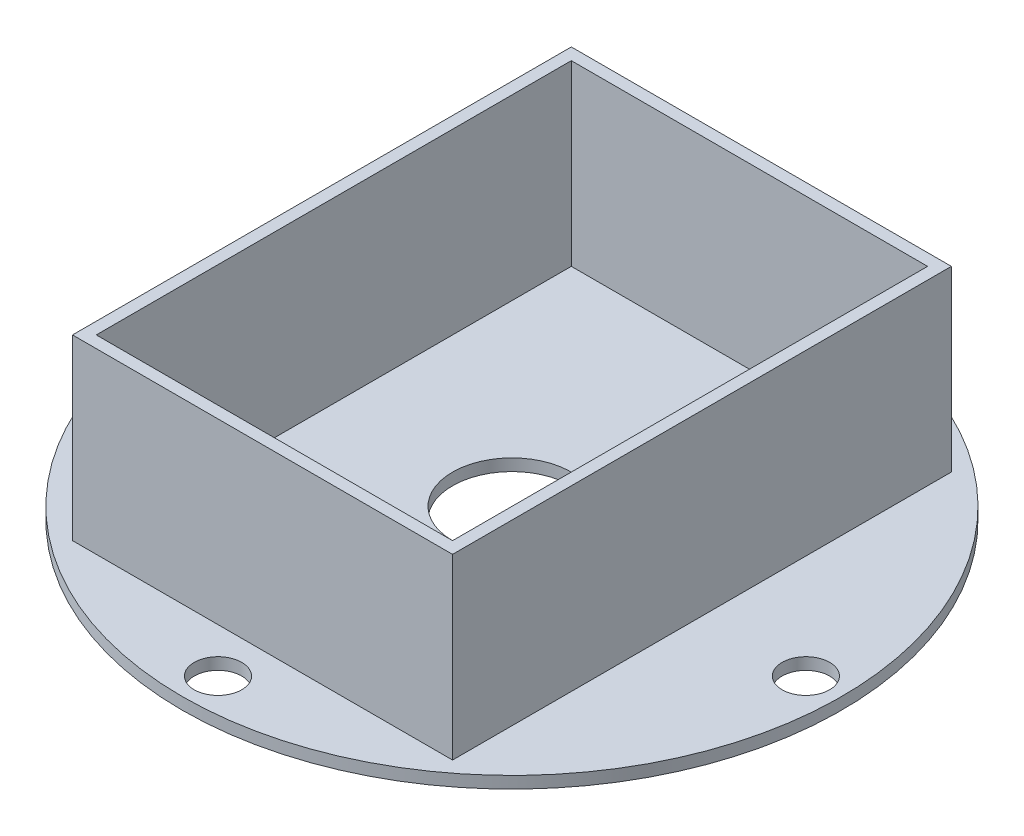
SolidWorks part; units mm, degrees
ref_plane "Front Plane" through (0, 0, 0) normal (0, 0, 1) x (1, 0, 0)
ref_plane "Top Plane" through (0, 0, 0) normal (0, 1, 0) x (1, 0, 0)
ref_plane "Right Plane" through (0, 0, 0) normal (1, 0, 0) x (0, 0, -1)
sketch "Sketch1" plane through (0, 0, 0) normal (0, 1, 0) x (1, 0, 0)
  circle A0 centre (0, 0) radius 55.5
  circle A5 centre (0, 49.5) radius 4
  circle A6 centre (49.5, 0) radius 4
  circle A7 centre (-49.5, 0) radius 4
  circle A8 centre (0, -49.5) radius 4
  dimension "D1" = 111
  dimension "D3" = 8
  dimension "D4" = 8
  dimension "D5" = 8
  dimension "D6" = 8
extrude "Boss-Extrude4" add sketch "Sketch1" along normal blind 2
sketch "Sketch6" plane through (0, 2, 0) normal (0, 1, 0) x (1, 0, 0)
  line L1 (-30, 40) -> (30, 40)
  line L2 (-30, 40) -> (-30, -40)
  line L3 (-30, -40) -> (30, -40)
  line L4 (30, 40) -> (30, -40)
  line L5 (-30, 40) -> (30, -40) construction
  line L6 (-30, -40) -> (30, 40) construction
  line L7 (-32, 42) -> (32, 42)
  line L8 (-32, 42) -> (-32, -42)
  line L9 (-32, -42) -> (32, -42)
  line L10 (32, 42) -> (32, -42)
  line L11 (-32, 42) -> (32, -42) construction
  line L12 (-32, -42) -> (32, 42) construction
  point P0 (0, 0)
  point P6 (0, 0)
  dimension "D1" = 80
  dimension "D2" = 60
  dimension "D3" = 84
  dimension "D4" = 64
extrude "Boss-Extrude5" add sketch "Sketch6" along normal blind 30
sketch "Sketch7" plane through (0, 2, 0) normal (0, 1, 0) x (1, 0, 0)
  circle A0 centre (0, 0) radius 10
  dimension "D1" = 20
extrude "Cut-Extrude2" cut sketch "Sketch7" against normal blind 30
